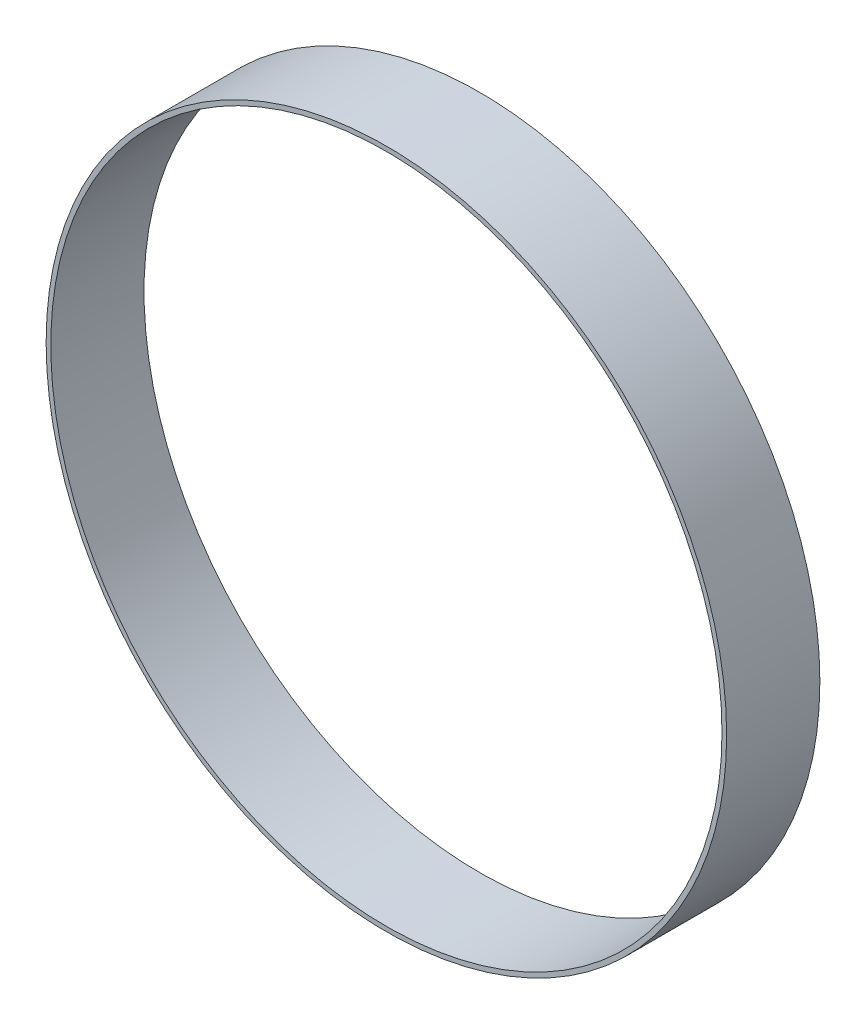
SolidWorks part; units mm, degrees
material "6061-T6 (SS)"
ref_plane "Front Plane" through (0, 0, 0) normal (0, 0, 1) x (1, 0, 0)
ref_plane "Top Plane" through (0, 0, 0) normal (0, 1, 0) x (1, 0, 0)
ref_plane "Right Plane" through (0, 0, 0) normal (1, 0, 0) x (0, 0, -1)
sketch "Sketch1" plane through (0, 0, 0) normal (0, 0, 1) x (1, 0, 0)
  circle A0 centre (0, 0) radius 72
  circle A1 centre (0, 0) radius 73
  dimension "D1" = 146
  dimension "D2" = 144
extrude "Boss-Extrude1" add sketch "Sketch1" along normal blind 20
